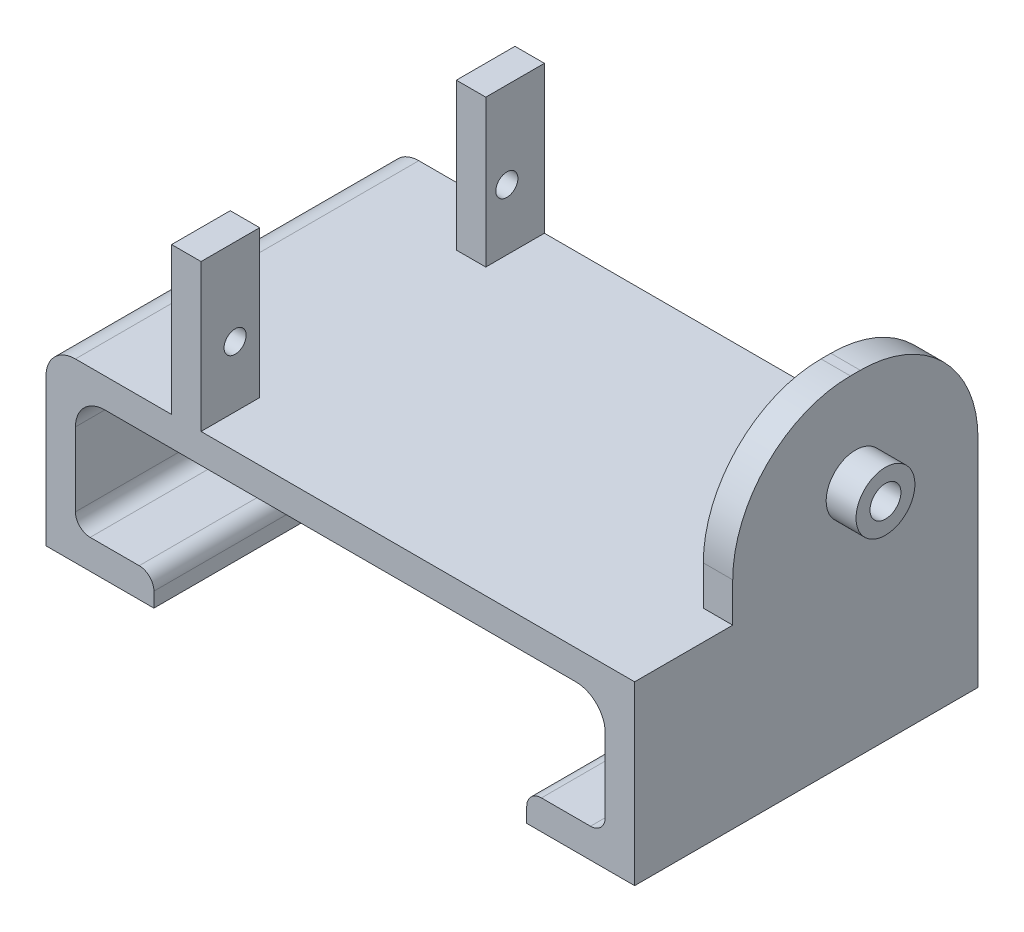
SolidWorks part; units mm, degrees
ref_plane "Front Plane" through (0, 0, 0) normal (0, 0, 1) x (1, 0, 0)
ref_plane "Top Plane" through (0, 0, 0) normal (0, 1, 0) x (1, 0, 0)
ref_plane "Right Plane" through (0, 0, 0) normal (1, 0, 0) x (0, 0, -1)
sketch "Sketch2" plane through (0, 0, 0) normal (0, 0, 1) x (1, 0, 0)
  line L0 (-30, 3) -> (-30, 21)
  line L3 (30, 3) -> (19, 3)
  line L5 (19, 3) -> (19, 6)
  line L6 (19, 6) -> (27, 6)
  line L7 (27, 6) -> (27, 18)
  line L8 (27, 18) -> (-27, 18)
  line L9 (-27, 18) -> (-27, 6)
  line L10 (-27, 6) -> (-19, 6)
  line L11 (-19, 6) -> (-19, 3)
  line L12 (-19, 3) -> (-30, 3)
  line L13 (27, 21) -> (27, 37)
  line L14 (27, 37) -> (30, 37)
  line L15 (30, 37) -> (30, 3)
  line L16 (27, 21) -> (-30, 21)
  dimension "D1" = 3
  dimension "D2" = 3
  dimension "D3" = 8
  dimension "D4" = 3
  dimension "D5" = 3
  dimension "D6" = 16
  dimension "D7" = 18
extrude "Boss-Extrude1" add sketch "Sketch2" against normal blind 35 contours L13 L16 L0 L12 L11 L10 L9 L8 L7 L6 L5 L3 L15 L14
sketch "Sketch3" plane through (0, 0, 0) normal (0, 1, 0) x (1, 0, 0)
  circle A0 centre (-22.45, 16) radius 1.575
  circle A1 centre (22.55, 16) radius 1.575
  dimension "D1" = 3.15
  dimension "D2" = 3.15
extrude "Cut-Extrude1" cut sketch "Sketch3" along normal blind 10
sketch "Sketch5" plane through (30, 0, 0) normal (1, 0, 0) x (0, 0, -1)
  line L0 (35, 37) -> (0, 37) construction
  line L5 (0, 37) -> (10, 37)
  line L6 (0, 37) -> (0, 21)
  line L7 (0, 21) -> (10, 21)
  line L8 (10, 37) -> (10, 21)
  line L9 (0, 37) -> (0, 3) construction
  dimension "D1" = 16
  dimension "D2" = 10
extrude "Cut-Extrude2" cut sketch "Sketch5" against normal blind 10 and the other way through all
fillet "Fillet2" radius 12 2 edges at (28.5, 37, -35) (28.5, 37, -10)
fillet "Fillet3" radius 3 3 edges at (27, 18, -17.5) (-27, 18, -17.5) (-30, 21, -17.5)
fillet "Fillet4" radius 1.5 4 edges at (27, 6, -17.5) (-27, 6, -17.5) (19, 6, -17.5) (-19, 6, -17.5)
sketch "Sketch6" plane through (0, 21, 0) normal (0, 1, 0) x (1, 0, 0)
  line L0 (-27, 17.5) -> (46.0655, 17.5) construction
  line L1 (-27, 35) -> (-27, 0) construction
  line L2 (27, 35) -> (-27, 35) construction
  line L3 (-17.1962, 35) -> (-14.1962, 35)
  line L4 (-17.1962, 35) -> (-17.1962, 29.0233)
  line L5 (-17.1962, 29.0233) -> (-14.1962, 29.0233)
  line L6 (-14.1962, 35) -> (-14.1962, 29.0233)
  line L7 (-17.2962, 28.7233) -> (0.0038, 28.7233) construction
  line L8 (-17.4962, 33.1733) -> (-17.4962, 28.9161) construction
  line L9 (-17.1962, 5.9767) -> (-14.1962, 5.9767)
  line L10 (-14.1962, 0) -> (-14.1962, 5.9767)
  line L11 (-17.1962, 0) -> (-14.1962, 0)
  line L12 (-17.1962, 0) -> (-17.1962, 5.9767)
  line M6 (27, 35) -> (-27, 35)
  line M8 (-27, 0) -> (30, 0)
  dimension "D1" = 3
  dimension "D2" = 0.3
  dimension "D3" = 0.3
extrude "Boss-Extrude2" add sketch "Sketch6" along normal blind 15 contours L6 L4 L5 M6 | L12 L10 L9 M8
sketch "Sketch8" plane through (0, 0, 0) normal (1, 0, 0) x (0, 0, -1)
  circle A0 centre (3.4733, 27.2) radius 1.125
  circle A1 centre (31.1733, 27.2) radius 1.125
  dimension "D1" = 2.25
  dimension "D2" = 2.25
extrude "Cut-Extrude3" cut sketch "Sketch8" against normal blind 25
sketch "Sketch10" plane through (30, 0, 0) normal (1, 0, 0) x (0, 0, -1)
  circle A0 centre (22.5233, 27.2) radius 3
  dimension "D1" = 6
extrude "Boss-Extrude3" add sketch "Sketch10" along normal up to surface (3.0444 mm away) contours A0
sketch "Sketch11" plane through (30, 0, 0) normal (1, 0, 0) x (0, 0, -1)
  circle A0 centre (22.5233, 27.2) radius 1.575
  dimension "D1" = 3.15
extrude "Cut-Extrude4" cut sketch "Sketch11" along direction (1, 0, 0) on the side of the normal mid plane 15 contours A0
